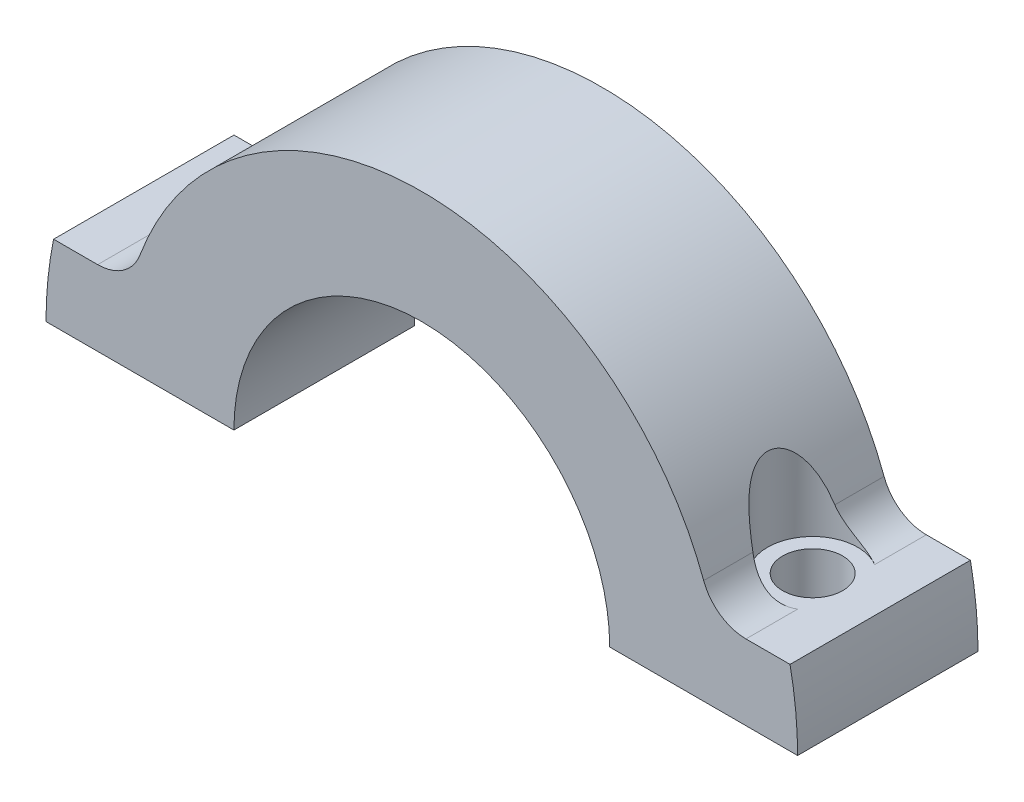
SolidWorks part; units mm, degrees
ref_plane "Front Plane" through (0, 0, 0) normal (0, 0, 1) x (1, 0, 0)
ref_plane "Top Plane" through (0, 0, 0) normal (0, 1, 0) x (1, 0, 0)
ref_plane "Right Plane" through (0, 0, 0) normal (1, 0, 0) x (0, 0, -1)
sketch "Sketch2" plane through (0, 0, 0) normal (0, 0, 1) x (1, 0, 0)
  line L0 (-25, 0) -> (-12.5, 0)
  line L1 (-24.4949, 5) -> (-21.5639, 5)
  line L2 (12.5, 0) -> (25, 0)
  line L3 (21.5639, 5) -> (24.4949, 5)
  arc A0 (12.5, 0) -> (-12.5, 0) centre (0, 0) ccw
  arc A1 (18.7512, 6.9565) -> (-18.7512, 6.9565) centre (0, 0) ccw
  arc A2 (25, 0) -> (24.4949, 5) centre (0, 0) ccw
  arc A3 (-24.4949, 5) -> (-25, 0) centre (0, 0) ccw
  arc A4 (21.5639, 5) -> (18.7512, 6.9565) centre (21.5639, 8) cw
  arc A5 (-21.5639, 5) -> (-18.7512, 6.9565) centre (-21.5639, 8) ccw
  dimension "D1" = 40
  dimension "D2" = 25
  dimension "D3" = 50
  dimension "D5" = 3
  dimension "D4" = 5
extrude "Boss-Extrude1" add sketch "Sketch2" along normal blind 12
sketch "Sketch3" plane through (0, 0, 0) normal (0, 1, 0) x (1, 0, 0)
  line L0 (0, 0) -> (0, -12) construction
  line L1 (18.7512, 0) -> (-18.7512, 0) construction
  line L2 (-18.7512, -12) -> (18.7512, -12) construction
  circle A0 centre (20, -6) radius 2
  circle A1 centre (-20, -6) radius 2
  dimension "D1" = 4
  dimension "D2" = 20
  dimension "D3" = 6
extrude "Cut-Extrude1" cut sketch "Sketch3" along normal blind 10
sketch "Sketch4" plane through (0, 5, 0) normal (0, 1, 0) x (1, 0, 0)
  circle A0 centre (20, -6) radius 3
  circle A1 centre (-20, -6) radius 3
  dimension "D1" = 6
  dimension "D2" = 6
extrude "Cut-Extrude2" cut sketch "Sketch4" along normal blind 10
